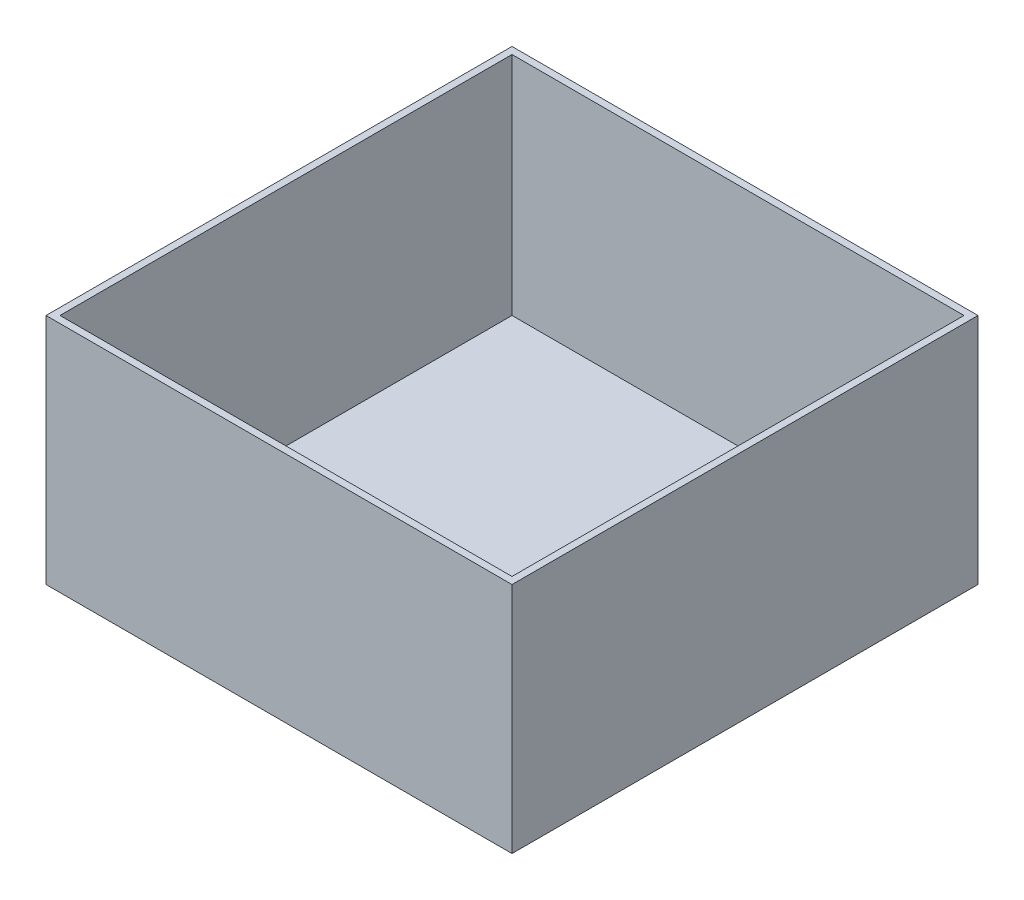
SolidWorks part; units mm, degrees
material "ABS"
ref_plane "Front Plane" through (0, 0, 0) normal (0, 0, 1) x (1, 0, 0)
ref_plane "Top Plane" through (0, 0, 0) normal (0, 1, 0) x (1, 0, 0)
ref_plane "Right Plane" through (0, 0, 0) normal (1, 0, 0) x (0, 0, -1)
sketch "Sketch1" plane through (0, 0, 0) normal (0, 1, 0) x (1, 0, 0)
  line L0 (-100, 100) -> (-100, -100)
  line L1 (-100, -100) -> (100, -100)
  line L2 (100, -100) -> (100, 100)
  line L3 (100, 100) -> (-100, 100)
  point P4 (-100, 0)
  point P6 (0, 100)
  dimension "D1" = 200
extrude "Boss-Extrude1" add sketch "Sketch1" along normal blind 100
sketch "Sketch2" plane through (0, 100, 0) normal (0, 1, 0) x (1, 0, 0)
  line L0 (97, 97) -> (-97, 97)
  line L1 (-97, 97) -> (-97, -97)
  line L2 (-97, -97) -> (97, -97)
  line L3 (97, -97) -> (97, 97)
  line L4 (100, 100) -> (-100, 100)
  line L5 (-100, 100) -> (-100, -100)
  line L6 (-100, -100) -> (100, -100)
  line L7 (100, -100) -> (100, 100)
  line L8 (100, 100) -> (-100, 100) construction
  line L9 (-100, 100) -> (-100, -100) construction
  line L10 (-100, -100) -> (100, -100) construction
  line L11 (100, -100) -> (100, 100) construction
  dimension "D1" = 0
  dimension "D2" = 3
extrude "Cut-Extrude1" cut sketch "Sketch2" against normal blind 97
